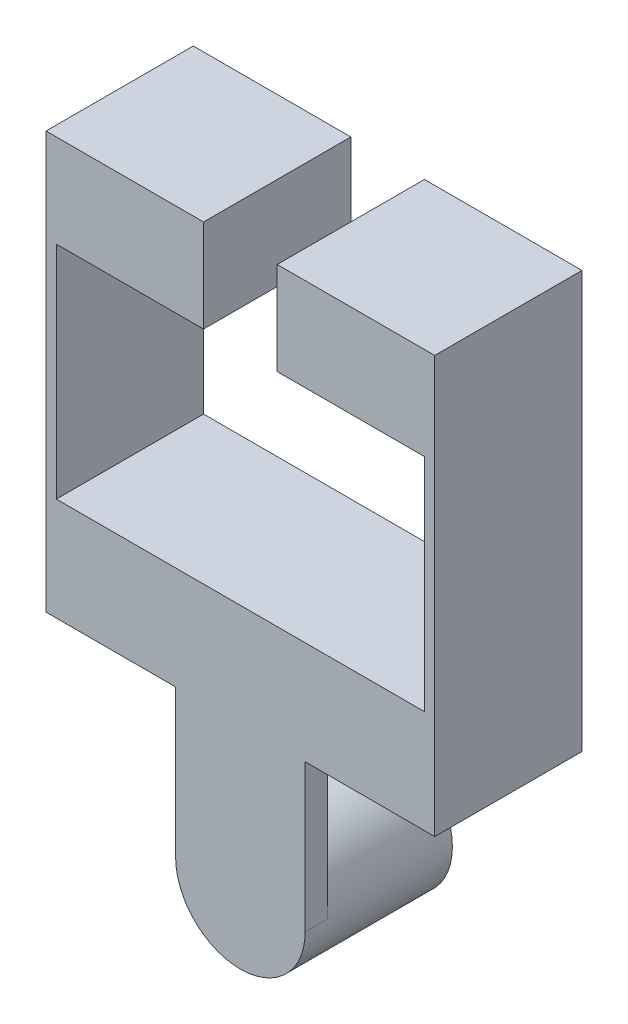
SolidWorks part; units mm, degrees
material "ASTM A36 Steel"
ref_plane "Front Plane" through (0, 0, 0) normal (0, 0, 1) x (1, 0, 0)
ref_plane "Top Plane" through (0, 0, 0) normal (0, 1, 0) x (1, 0, 0)
ref_plane "Right Plane" through (0, 0, 0) normal (1, 0, 0) x (0, 0, -1)
sketch "Sketch1" plane through (0, 0, 0) normal (0, 0, 1) x (1, 0, 0)
  line L0 (-12.0433, 53.9479) -> (15.1347, 53.9479)
  line L1 (15.1347, 53.9479) -> (15.1347, -17.9341)
  line L3 (-51.9213, -17.9341) -> (-51.9213, 53.9479)
  line L4 (-51.9213, 53.9479) -> (-24.7433, 53.9479)
  line L5 (-24.7433, 53.9479) -> (-24.7433, 37.9459)
  line L6 (-24.7433, 37.9459) -> (-50.1433, 37.9459)
  line L7 (-50.1433, 37.9459) -> (-50.1433, -0.1541)
  line L8 (-50.1433, -0.1541) -> (13.3567, -0.1541)
  line L9 (13.3567, -0.1541) -> (13.3567, 37.9459)
  line L10 (13.3567, 37.9459) -> (-12.0433, 37.9459)
  line L11 (-12.0433, 37.9459) -> (-12.0433, 53.9479)
  line L16 (-18.3933, -17.9341) -> (-18.3933, 53.9479) construction
  line L17 (-51.9213, -17.9341) -> (15.1347, -17.9341)
  dimension "D2" = 67.056
  dimension "D5" = 63.5
  dimension "D6" = 38.1
  dimension "D7" = 38.1
  dimension "D8" = 1.778
  dimension "D9" = 1.778
  dimension "D10" = 16.002
  dimension "D11" = 16.002
  dimension "D12" = 25.4
  dimension "D13" = 25.4
extrude "Boss-Extrude2" add sketch "Sketch1" along normal blind 25.4 contours L17 L1 L0 L11 L10 L9 L8 L7 L6 L5 L4 L3
sketch "Sketch2" plane through (0, 0, 25.4) normal (0, 0, 1) x (1, 0, 0)
  line L0 (-18.3933, -17.9341) -> (-18.3933, 54.2273) construction
  line L1 (-51.9213, -17.9341) -> (15.1347, -17.9341) construction
  line L2 (-29.5693, -17.9341) -> (-29.5693, -43.3341)
  line L3 (-29.5693, -43.3341) -> (-7.2173, -43.3341)
  line L4 (-7.2173, -43.3341) -> (-7.2173, -17.9341)
  line L5 (-7.2173, -17.9341) -> (-29.5693, -17.9341)
  line L6 (-18.3933, -17.9341) -> (-18.3933, -43.3341) construction
  dimension "D1" = 25.4
  dimension "D2" = 22.352
extrude "Boss-Extrude3" add sketch "Sketch2" against normal blind 3.81
sketch "Sketch5" plane through (0, 0, 25.4) normal (0, 0, 1) x (1, 0, 0)
  line L0 (-29.5693, -43.3341) -> (-7.2173, -43.3341) construction
  circle A0 centre (-18.3933, -43.3341) radius 11.176
  dimension "D1" = 22.352
extrude "Boss-Extrude6" add sketch "Sketch5" against normal blind 25.4
equation "\"F\"= 600'force"
equation "\"Sy\"= 36259.43'yield strength"
equation "\"SF\"= 4'safety factor"
equation "\"E\"= 29007547.53'elastic modulus"
equation "\"Def\"= .005'deflection"
equation "\"A length\"= 1"
equation "\"b length\"= 1"
equation "\"c length\"= 2.5"
equation "\"c width\"= 1"
equation "\"d width\"= 1"
equation "\"d height\"= 1.5"
equation "\"e width\"= 1"
equation "\"e length\"= .9990"
equation "\"Za\"= \"SF\" * 2 * \"F\" * \"A length\" / ( 2 * \"Sy\" )"
equation "\"a radius\"= ( 4 * \"Za\" / PI ) ^ ( 1 / 3 )"
equation "\"a diameter\"= 2 * \"a radius\""
equation "\"b width\"= \"a diameter\""
equation "\"b stress\"= \"Sy\" / \"SF\""
equation "\"b area\"= ( 2 * \"F\" ) / \"b stress\""
equation "\"b thickness\"= \"b area\" / \"b width\""
equation "\"c stress\"= \"Sy\" / \"SF\""
equation "\"c moment\"= ( 2 * \"F\" ) * \"c length\" / 4"
equation "\"Zc\"= \"c moment\" / \"c stress\""
equation "\"c height\"= ( 6 * \"Zc\" / \"c width\" ) ^ ( 1 / 2 )"
equation "\"d stress\"= \"Sy\" / \"SF\""
equation "\"d area\"= \"F\" / \"d stress\""
equation "\"d length\"= \"d area\" / \"d width\""
equation "\"e stress\"= \"Sy\" / \"SF\""
equation "\"e moment\"= \"F\" * \"e length\""
equation "\"e height\"= ( 6 * \"e moment\" / ( \"e width\" * \"e stress\" ) ) ^ ( 1 / 2 )"
